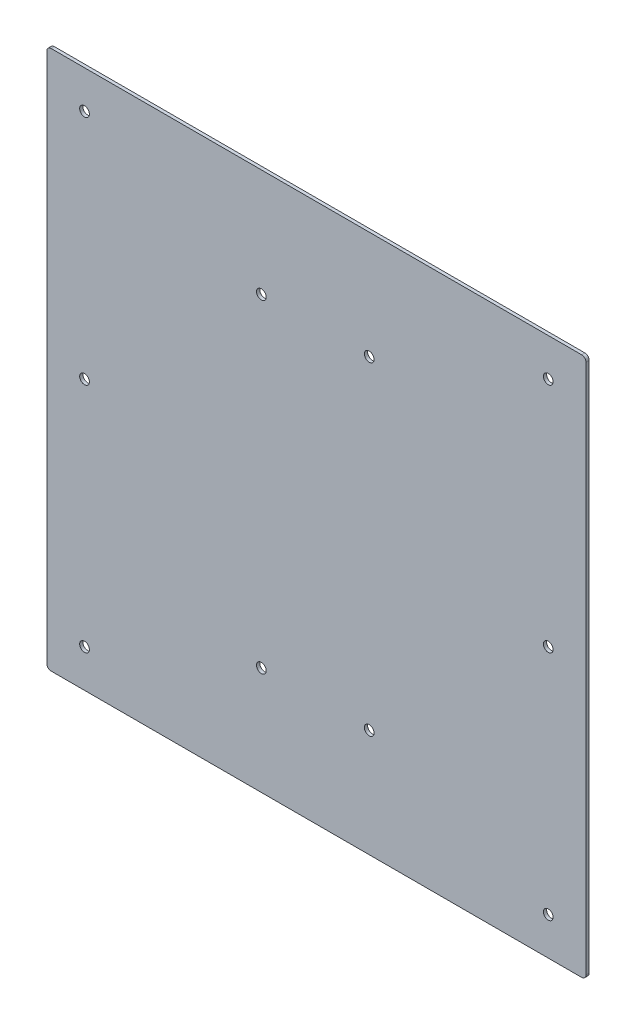
SolidWorks part; units mm, degrees
ref_plane "Front Plane" through (0, 0, 0) normal (0, 0, 1) x (1, 0, 0)
ref_plane "Top Plane" through (0, 0, 0) normal (0, 1, 0) x (1, 0, 0)
ref_plane "Right Plane" through (0, 0, 0) normal (1, 0, 0) x (0, 0, -1)
sketch "Sketch1" plane through (0, 0, 0) normal (0, 0, 1) x (1, 0, 0)
  line L1 (-125, -125) -> (125, -125)
  line L2 (-125, -125) -> (-125, 125)
  line L3 (-125, 125) -> (125, 125)
  line L4 (125, -125) -> (125, 125)
  line L5 (-125, -125) -> (125, 125) construction
  line L6 (-125, 125) -> (125, -125) construction
  circle A0 centre (-25.5, 75) radius 2.25
  circle A1 centre (24.5, 75) radius 2.25
  circle A2 centre (24.5, -75) radius 2.25
  circle A3 centre (-25.5, -75) radius 2.25
  point P0 (0, 0)
  dimension "D1" = 150
  dimension "D7" = 4.5
  dimension "D2" = 50
  dimension "D3" = 25.5
  dimension "D4" = 75
  dimension "D5" = 250
  dimension "D6" = 250
extrude "Boss-Extrude1" add sketch "Sketch1" along normal blind 1.4986
fillet "Fillet1" radius 2 4 edges at (-125, -125, 0.7493) (125, -125, 0.7493) (125, 125, 0.7493) (-125, 125, 0.7493)
sketch "Sketch2" plane through (0, 0, 1.4986) normal (0, 0, 1) x (1, 0, 0)
  line L0 (-123, -125) -> (123, -125) construction
  line L1 (-125, 123) -> (-125, -123) construction
  line L2 (123, 125) -> (-123, 125) construction
  line L3 (125, -123) -> (125, 123) construction
  circle A0 centre (-107.5, 107.5) radius 2.25
  circle A1 centre (107.5, 107.5) radius 2.25
  circle A2 centre (107.5, -107.5) radius 2.25
  circle A3 centre (-107.5, -107.5) radius 2.25
  circle A4 centre (-107.5, 0) radius 2.25
  circle A5 centre (107.5, 0) radius 2.25
  dimension "D1" = 4.5
  dimension "D2" = 17.5
  dimension "D3" = 17.5
  dimension "D4" = 17.5
  dimension "D5" = 17.5
extrude "Cut-Extrude1" cut sketch "Sketch2" against normal up to surface (1.4986 mm away) up to face at (26.75, -75, 0)
